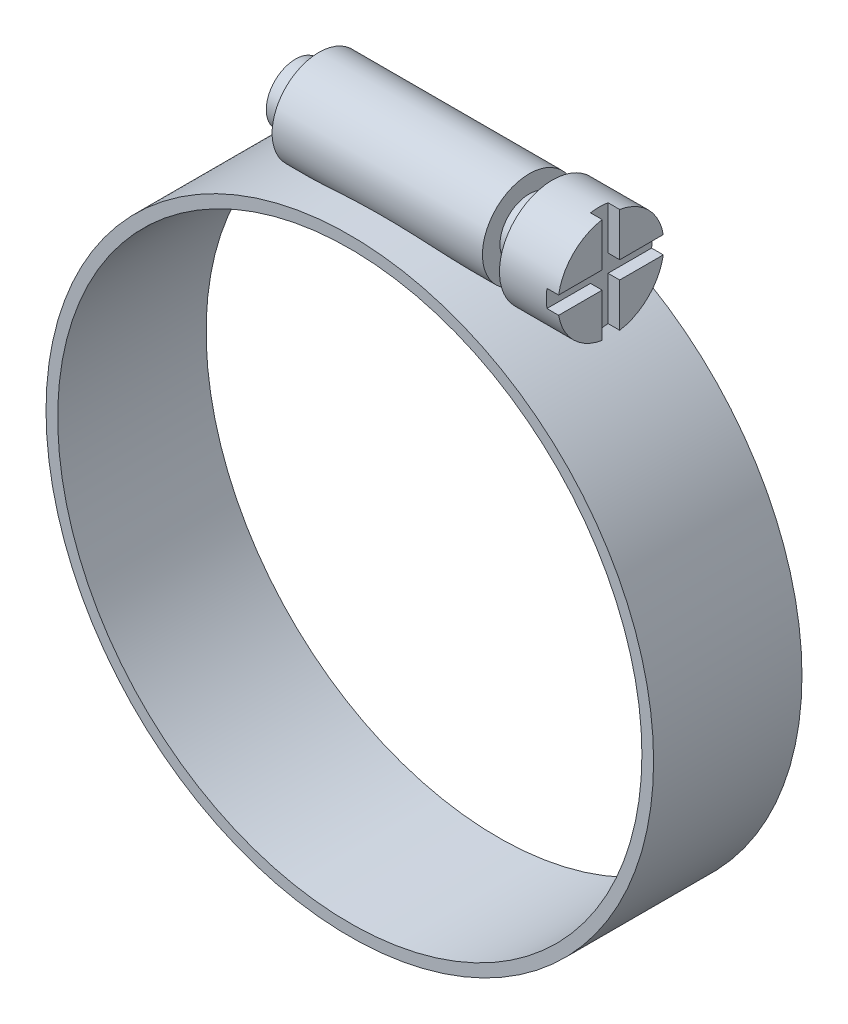
SolidWorks part; units mm, degrees
material "316 S/Steel"
ref_plane "Front Plane" through (0, 0, 0) normal (0, 0, 1) x (1, 0, 0)
ref_plane "Top Plane" through (0, 0, 0) normal (0, 1, 0) x (1, 0, 0)
ref_plane "Right Plane" through (0, 0, 0) normal (1, 0, 0) x (0, 0, -1)
sketch "Sketch1" plane through (0, 0, 0) normal (1, 0, 0) x (0, 0, -1)
  line L0 (0, 0) -> (80.0928, 0) construction
  line L1 (0, 0) -> (0, 28.8457) construction
  line L2 (-6.35, 26) -> (6.35, 26)
  line L3 (-6.35, 26) -> (-6.35, 25)
  line L4 (-6.35, 25) -> (6.35, 25)
  line L5 (6.35, 26) -> (6.35, 25)
  dimension "D1" = 50
  dimension "D2" = 1
  dimension "D3" = 12.7
revolve "Revolve1" add sketch "Sketch1" angle 360 about L0
sketch "Sketch2" plane through (0, 0, 0) normal (1, 0, 0) x (0, 0, -1)
  circle A0 centre (0, 27.8676) radius 4
  dimension "D1" = 27.8676
  dimension "D2" = 8
extrude "Boss-Extrude1" add sketch "Sketch2" along normal mid plane 18
sketch "Sketch3" plane through (9, 0, 0) normal (1, 0, 0) x (0, 0, -1)
  circle A0 centre (0, 27.8676) radius 2.5
  dimension "D1" = 5
extrude "Boss-Extrude2" add sketch "Sketch3" along normal blind 2 and the other way offset from surface (20 mm away) 2 other way up to face at (-9, 28.1301, 0)
sketch "Sketch4" plane through (11, 0, 0) normal (1, 0, 0) x (0, 0, -1)
  circle A0 centre (0, 27.8676) radius 4.5408
extrude "Boss-Extrude3" add sketch "Sketch4" along normal blind 5
sketch "Sketch5" plane through (16, 0, 0) normal (1, 0, 0) x (0, 0, -1)
  line L0 (0, 32.4084) -> (0, 27.8676) construction
  line L1 (0, 27.8676) -> (9.7523, 27.8676) construction
  line L2 (0.75, 27.1176) -> (5.5888, 27.1176)
  line L3 (-0.75, 32.8819) -> (0.75, 32.8819)
  line L4 (-0.75, 32.8819) -> (-0.75, 28.6176)
  line L5 (-0.75, 22.8534) -> (0.75, 22.8534)
  line L6 (0.75, 32.8819) -> (0.75, 28.6176)
  line L7 (-5.5888, 28.6176) -> (-0.75, 28.6176)
  line L8 (-5.5888, 28.6176) -> (-5.5888, 27.1176)
  line L9 (-5.5888, 27.1176) -> (-0.75, 27.1176)
  line L10 (5.5888, 28.6176) -> (5.5888, 27.1176)
  line L11 (-0.75, 27.1176) -> (-0.75, 22.8534)
  line L12 (0.75, 28.6176) -> (5.5888, 28.6176)
  line L13 (0.75, 27.1176) -> (0.75, 22.8534)
  circle A0 centre (0, 27.8676) radius 4.5408 construction
  dimension "D1" = 1.5
  dimension "D2" = 1.5
  dimension "D3" = 10.0285
  dimension "D4" = 11.1776
extrude "Cut-Extrude1" cut sketch "Sketch5" against normal blind 1
